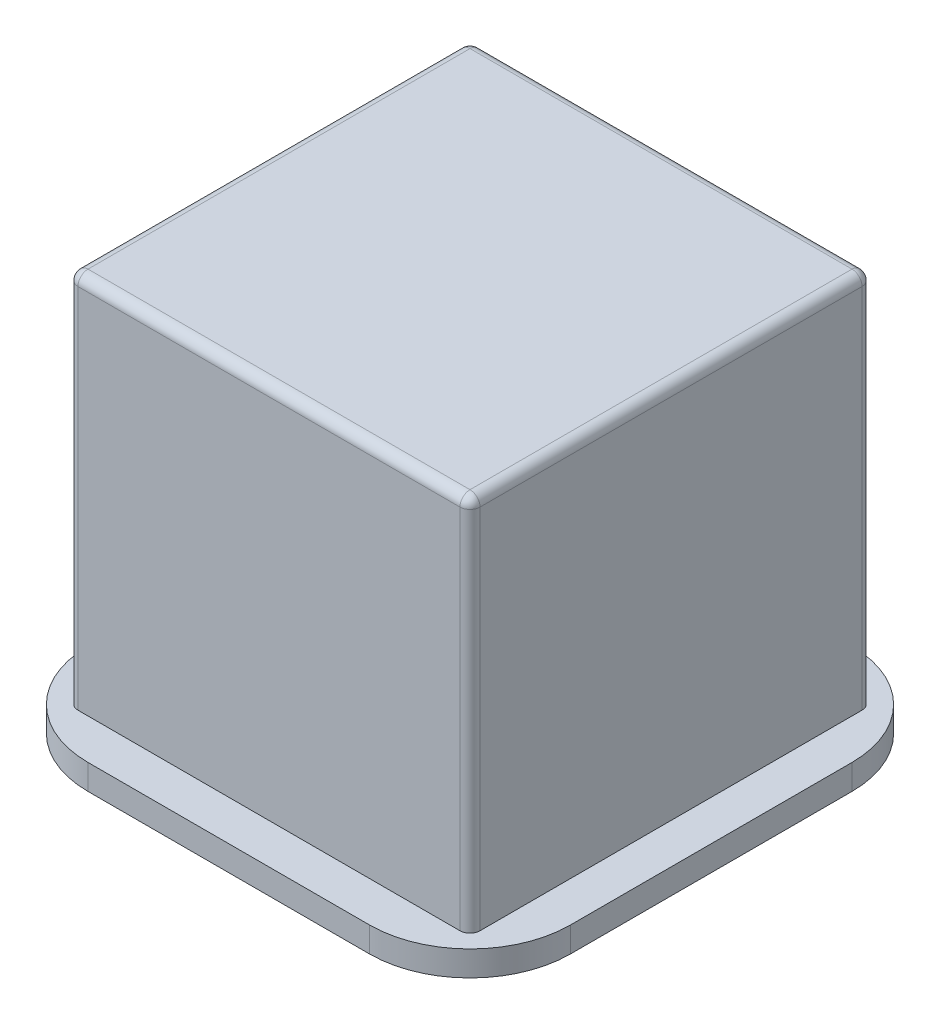
SolidWorks part; units mm, degrees
ref_plane "Front Plane" through (0, 0, 0) normal (0, 0, 1) x (1, 0, 0)
ref_plane "Top Plane" through (0, 0, 0) normal (0, 1, 0) x (1, 0, 0)
ref_plane "Right Plane" through (0, 0, 0) normal (1, 0, 0) x (0, 0, -1)
sketch "Sketch1" plane through (0, 0, 0) normal (0, 1, 0) x (1, 0, 0)
  line L1 (0, 0) -> (200, 0)
  line L2 (0, 0) -> (0, 200)
  line L3 (0, 200) -> (200, 200)
  line L4 (200, 0) -> (200, 200)
  dimension "D1" = 200
  dimension "D2" = 200
extrude "Boss-Extrude1" add sketch "Sketch1" along normal blind 200
sketch "Sketch3" plane through (0, 0, 0) normal (0, 0, 1) x (1, 0, 0)
  line L0 (200, 200) -> (200, 0) construction
  line L1 (0, 0) -> (200, 0)
  line L2 (0, 0) -> (0, 12.5)
  line L3 (0, 12.5) -> (200, 12.5)
  line L4 (200, 0) -> (200, 12.5)
  dimension "D1" = 12.5
extrude "Boss-Extrude2" add sketch "Sketch3" along normal blind 20
sketch "Sketch4" plane through (200, 0, 0) normal (1, 0, 0) x (0, 0, -1)
  line L1 (-20, 12.5) -> (200, 12.5)
  line L2 (-20, 12.5) -> (-20, 0)
  line L3 (-20, 0) -> (200, 0)
  line L4 (200, 12.5) -> (200, 0)
extrude "Boss-Extrude3" add sketch "Sketch4" along normal blind 20
sketch "Sketch5" plane through (0, 0, -200) normal (0, 0, -1) x (-1, 0, 0)
  line L1 (-220, 12.5) -> (0, 12.5)
  line L2 (-220, 12.5) -> (-220, 0)
  line L3 (-220, 0) -> (0, 0)
  line L4 (0, 12.5) -> (0, 0)
extrude "Boss-Extrude4" add sketch "Sketch5" along normal blind 20
sketch "Sketch6" plane through (0, 0, 0) normal (-1, 0, 0) x (0, 0, 1)
  line L1 (-220, 12.5) -> (20, 12.5)
  line L2 (-220, 12.5) -> (-220, 0)
  line L3 (-220, 0) -> (20, 0)
  line L4 (20, 12.5) -> (20, 0)
extrude "Boss-Extrude5" add sketch "Sketch6" along normal blind 20
fillet "Fillet1" radius 50 4 edges at (220, 6.25, 20) (-20, 6.25, 20) (220, 6.25, -220) (-20, 6.25, -220)
fillet "Fillet2" radius 5 8 edges at (200, 106.25, -200) (200, 106.25, 0) (100, 200, -200) (200, 200, -100) (0, 106.25, -200) (0, 200, -100) (100, 200, 0) (0, 106.25, 0)
shell "Shell1" thickness 4
